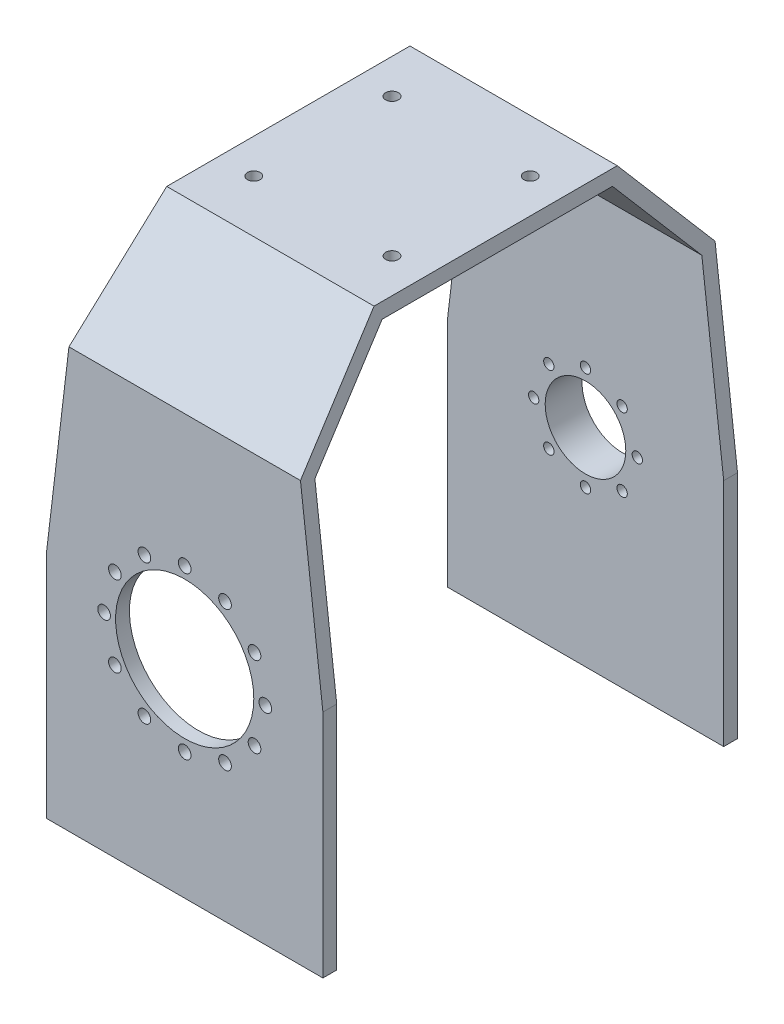
SolidWorks part; units mm, degrees
ref_plane "前视基准面" through (0, 0, 0) normal (0, 0, 1) x (1, 0, 0)
ref_plane "上视基准面" through (0, 0, 0) normal (0, 1, 0) x (1, 0, 0)
ref_plane "右视基准面" through (0, 0, 0) normal (1, 0, 0) x (0, 0, -1)
other "Configuration Table"
sketch "草图11" plane through (0, 0, 0) normal (1, 0, 0) x (0, 0, -1)
  line L0 (0, 0) -> (0, 82.4039) construction
  line L1 (-50, 220.5196) -> (50, 220.5196)
  line L2 (50, 220.5196) -> (84, 180)
  line L3 (84, 180) -> (84, 0)
  line L4 (-84, 180) -> (-84, 0)
  line L5 (-50, 220.5196) -> (-84, 180)
  point P3 (80, 0)
  point P10 (0, 220.5196)
  point P11 (0, 0)
  dimension "D1" = 84
  dimension "D2" = 180
  dimension "D3" = 100
  dimension "D4" = 40
extrude "拉伸-薄壁1" add sketch "草图11" along normal blind 180 thin thin type one direction wall 6
sketch "草图12" plane through (0, 0, 0) normal (0, 0, 1) x (1, 0, 0)
  line L0 (90, 283.6741) -> (90, -81.1896) construction
  line L1 (180, 182.1838) -> (180, 0) construction
  line L2 (0, 182.1838) -> (0, 0) construction
  line L4 (180, 226.5196) -> (0, 226.5196) construction
  line L5 (0, 0) -> (0, 226.5196)
  line L6 (0, 226.5196) -> (0, 182.1838) construction
  line L7 (0, 226.5196) -> (45, 226.5196)
  line L12 (180, 0) -> (0, 0) construction
  line L13 (30, 0) -> (0, 0)
  line L14 (150, 0) -> (180, 0)
  line L15 (180, 0) -> (180, 226.5196)
  line L16 (180, 226.5196) -> (135, 226.5196)
  line L18 (45, 226.5196) -> (30, 100)
  line L19 (30, 100) -> (30, 0)
  line L20 (150, 100) -> (150, 0)
  line L21 (135, 226.5196) -> (150, 100)
  circle A0 centre (90, 90) radius 45 construction
  dimension "D1" = 90
  dimension "D2" = 90
  dimension "D3" = 90
  dimension "D4" = 100
  dimension "D5" = 30
extrude "切除-拉伸1" cut sketch "草图12" against normal through all both and the other way through all
sketch "草图14" plane through (0, 0, 90) normal (0, 0, 1) x (1, 0, 0)
  line L0 (90, 90) -> (90, 146.2724) construction
  line L1 (90, 283.6741) -> (90, -81.1896) construction
  circle A0 centre (90, 90) radius 30
  circle A2 centre (90, 90) radius 35 construction
  circle A11 centre (90, 125) radius 2.75
  circle A12 centre (107.5, 120.3109) radius 2.75
  circle A13 centre (120.3109, 107.5) radius 2.75
  circle A14 centre (125, 90) radius 2.75
  circle A15 centre (120.3109, 72.5) radius 2.75
  circle A16 centre (107.5, 59.6891) radius 2.75
  circle A17 centre (90, 55) radius 2.75
  circle A18 centre (72.5, 59.6891) radius 2.75
  circle A19 centre (59.6891, 72.5) radius 2.75
  circle A20 centre (55, 90) radius 2.75
  circle A21 centre (59.6891, 107.5) radius 2.75
  circle A22 centre (72.5, 120.3109) radius 2.75
  point P9 (90, 90)
  point P10 (90, 90)
  point P11 (90, 90)
  point P26 (90, 90)
  point P35 (90, 90)
  point P36 (120.3109, 107.5)
  dimension "D1" = 60
  dimension "D2" = 70
  dimension "D3" = 5.5
  dimension "D4" = 12
extrude "切除-拉伸3" cut sketch "草图14" against normal blind 50
sketch "草图15" plane through (0, 0, -90) normal (0, 0, -1) x (-1, 0, 0)
  circle A0 centre (-90, 90) radius 27.5
  dimension "D1" = 55
extrude "凸台-拉伸3" add sketch "草图15" along normal blind 10
sketch "草图16" plane through (0, 0, -100) normal (0, 0, -1) x (-1, 0, 0)
  line L0 (-90, 90) -> (-36.3801, 90) construction
  line L1 (-90, 90) -> (-90, 130.4972) construction
  line L2 (-90, 283.6741) -> (-90, -81.1896) construction
  circle A0 centre (-90, 90) radius 17.5
  circle A1 centre (-67.5, 90) radius 2.25
  circle A2 centre (-74.0901, 74.0901) radius 2.25
  circle A3 centre (-90, 67.5) radius 2.25
  circle A4 centre (-105.9099, 74.0901) radius 2.25
  circle A5 centre (-112.5, 90) radius 2.25
  circle A6 centre (-105.9099, 105.9099) radius 2.25
  circle A7 centre (-90, 112.5) radius 2.25
  circle A8 centre (-74.0901, 105.9099) radius 2.25
  point P10 (-90, 90)
  point P25 (-90, 90)
  dimension "D1" = 35
  dimension "D2" = 4.5
  dimension "D3" = 22.5
  dimension "D4" = 8
extrude "切除-拉伸4" cut sketch "草图16" against normal blind 32.5
sketch "草图17" plane through (0, 226.5196, 0) normal (0, 1, 0) x (1, 0, 0)
  line L0 (25.9225, 0) -> (174.1323, 0) construction
  line L1 (90, -121.1832) -> (90, 132.8572) construction
  line L2 (135, 52.7978) -> (135, -52.7978) construction
  line L3 (45, 52.7978) -> (45, -52.7978) construction
  circle A0 centre (120, 30) radius 2.75
  circle A1 centre (120, -30) radius 2.75
  circle A2 centre (60, -30) radius 2.75
  circle A3 centre (60, 30) radius 2.75
  dimension "D1" = 5.5
  dimension "D2" = 60
  dimension "D3" = 60
extrude "切除-拉伸5" cut sketch "草图17" against normal up to surface (6 mm away) up to face at (90, 220.5196, 0)
